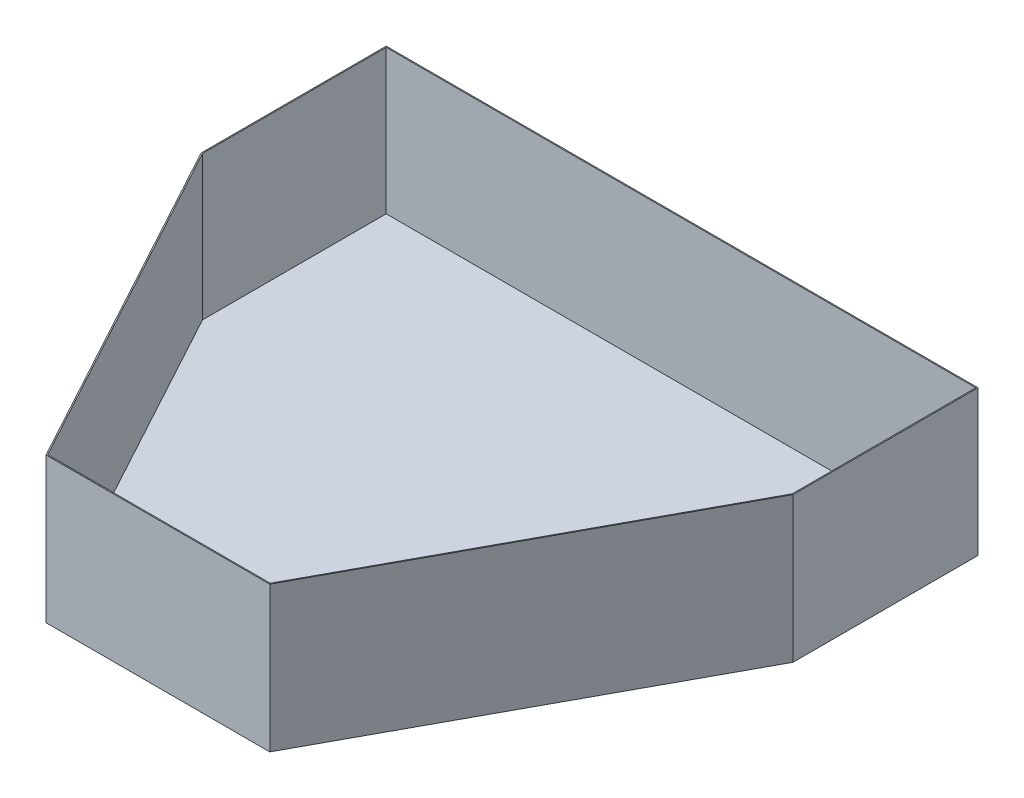
SolidWorks part; units mm, degrees
ref_plane "Front Plane" through (0, 0, 0) normal (0, 0, 1) x (1, 0, 0)
ref_plane "Top Plane" through (0, 0, 0) normal (0, 1, 0) x (1, 0, 0)
ref_plane "Right Plane" through (0, 0, 0) normal (1, 0, 0) x (0, 0, -1)
sketch "Sketch1" plane through (0, 0, 0) normal (0, 1, 0) x (1, 0, 0)
  line L0 (0, 0) -> (0, -1108.8933) construction
  line L1 (550, 0) -> (-550, 0)
  line L2 (-550, 0) -> (-550, -344)
  line L3 (-550, -344) -> (-208, -974.385)
  line L4 (-208, -974.385) -> (208, -974.385)
  line L5 (550, -344) -> (208, -974.385)
  line L6 (550, 0) -> (550, -344)
  point P8 (0, -974.385)
  dimension "D1" = 208
  dimension "D2" = 344
  dimension "D3" = 1100
extrude "Boss-Extrude1" add sketch "Sketch1" along normal mid plane 270
shell "Shell1" thickness 2
